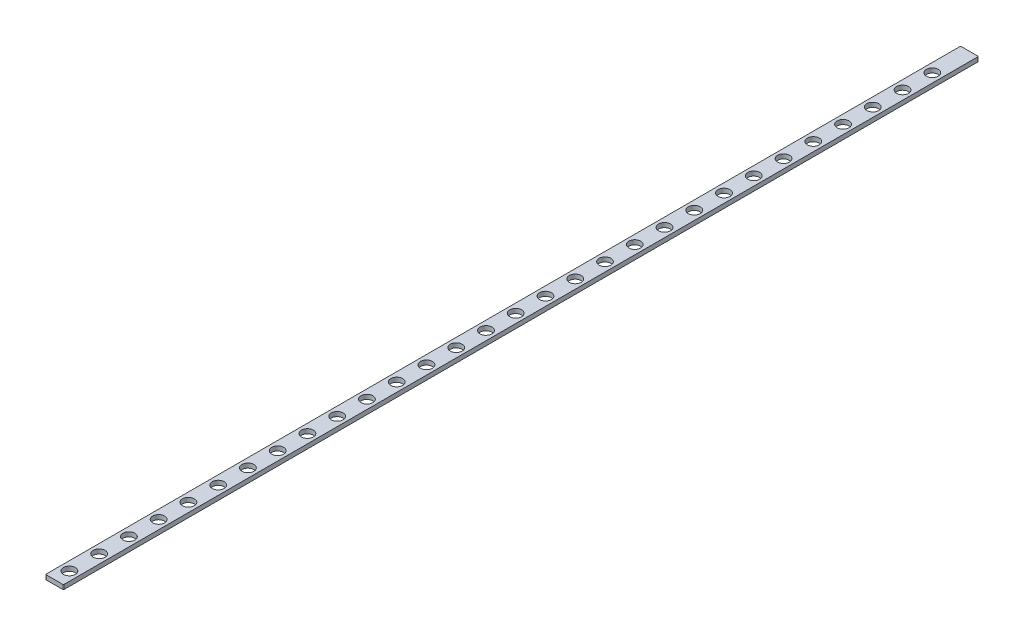
SolidWorks part; units mm, degrees
material "碳板"
ref_plane "前视基准面" through (0, 0, 0) normal (0, 0, 1) x (1, 0, 0)
ref_plane "上视基准面" through (0, 0, 0) normal (0, 1, 0) x (1, 0, 0)
ref_plane "右视基准面" through (0, 0, 0) normal (1, 0, 0) x (0, 0, -1)
sketch "草图1" plane through (0, 0, 0) normal (0, 1, 0) x (1, 0, 0)
  line L0 (0, -307.5) -> (0, -291.7228) construction
  line L1 (-6, 307.5) -> (6, 307.5)
  line L2 (-6, 307.5) -> (-6, -307.5)
  line L3 (-6, -307.5) -> (6, -307.5)
  line L4 (6, 307.5) -> (6, -307.5)
  line L5 (-6, 307.5) -> (6, -307.5) construction
  line L6 (-6, -307.5) -> (6, 307.5) construction
  line L7 (0, -297.5) -> (0, -277.5) construction
  circle A0 centre (0, -297.5) radius 4
  circle A1 centre (0, -277.5) radius 4
  circle A2 centre (0, -257.5) radius 4
  circle A3 centre (0, -237.5) radius 4
  circle A4 centre (0, -217.5) radius 4
  circle A5 centre (0, -197.5) radius 4
  circle A6 centre (0, -177.5) radius 4
  circle A7 centre (0, -157.5) radius 4
  circle A8 centre (0, -137.5) radius 4
  circle A9 centre (0, -117.5) radius 4
  circle A10 centre (0, -97.5) radius 4
  circle A11 centre (0, -77.5) radius 4
  circle A12 centre (0, -57.5) radius 4
  circle A13 centre (0, -37.5) radius 4
  circle A14 centre (0, -17.5) radius 4
  circle A15 centre (0, 2.5) radius 4
  circle A16 centre (0, 22.5) radius 4
  circle A17 centre (0, 42.5) radius 4
  circle A18 centre (0, 62.5) radius 4
  circle A19 centre (0, 82.5) radius 4
  circle A20 centre (0, 102.5) radius 4
  circle A21 centre (0, 122.5) radius 4
  circle A22 centre (0, 142.5) radius 4
  circle A23 centre (0, 162.5) radius 4
  circle A24 centre (0, 182.5) radius 4
  circle A25 centre (0, 202.5) radius 4
  circle A26 centre (0, 222.5) radius 4
  circle A27 centre (0, 242.5) radius 4
  circle A28 centre (0, 262.5) radius 4
  circle A29 centre (0, 282.5) radius 4
  point P0 (0, 0)
  dimension "D3" = 8
  dimension "D1" = 615
  dimension "D2" = 12
  dimension "D4" = 10
  dimension "D6" = 20
  dimension "D5" = 30
extrude "凸台-拉伸1" add sketch "草图1" along normal blind 3
fillet "圆角1" radius 0.5 4 edges at (-6, 1.5, 307.5) (-6, 1.5, -307.5) (6, 1.5, -307.5) (6, 1.5, 307.5)
